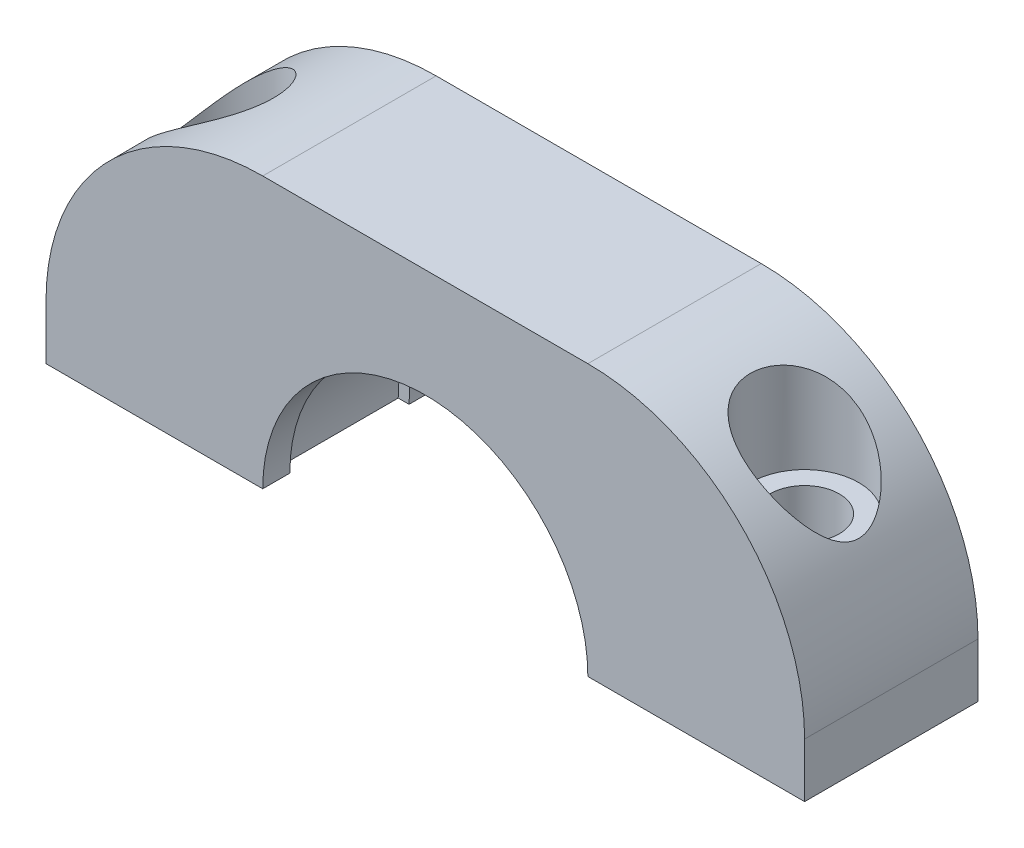
SolidWorks part; units mm, degrees
ref_plane "Front Plane" through (0, 0, 0) normal (0, 0, 1) x (1, 0, 0)
ref_plane "Top Plane" through (0, 0, 0) normal (0, 1, 0) x (1, 0, 0)
ref_plane "Right Plane" through (0, 0, 0) normal (1, 0, 0) x (0, 0, -1)
sketch "Sketch1" plane through (0, 0, 0) normal (0, 1, 0) x (1, 0, 0)
  line L1 (-17.5, -4) -> (17.5, -4)
  line L2 (-17.5, -4) -> (-17.5, 4)
  line L3 (-17.5, 4) -> (17.5, 4)
  line L4 (17.5, -4) -> (17.5, 4)
  line L5 (-17.5, -4) -> (17.5, 4) construction
  line L6 (-17.5, 4) -> (17.5, -4) construction
  point P0 (0, 0)
  dimension "D1" = 8
  dimension "D2" = 35
extrude "Boss-Extrude1" add sketch "Sketch1" along normal blind 12.5
sketch "Sketch2" plane through (0, 0, 4) normal (0, 0, 1) x (1, 0, 0)
  line L0 (-17.5, 0) -> (17.5, 0) construction
  circle A0 centre (0, 0) radius 7.5
  dimension "D1" = 15
extrude "Cut-Extrude1" cut sketch "Sketch2" against normal up to next
fillet "Fillet1" radius 10 2 edges at (17.5, 12.5, 0) (-17.5, 12.5, 0)
sketch "Sketch3" plane through (0, 0, 0) normal (0, 0, 1) x (1, 0, 0)
  circle A0 centre (0, 0) radius 8
  dimension "D1" = 16
extrude "Cut-Extrude2" cut sketch "Sketch3" against normal mid plane 5.5
sketch "Sketch4" plane through (0, 0, 0) normal (0, -1, 0) x (1, 0, 0)
  circle A0 centre (13.5, 0) radius 1.6
  circle A1 centre (-13.5, 0) radius 1.6
  dimension "D1" = 3.2
extrude "Cut-Extrude3" cut sketch "Sketch4" against normal through all
ref_plane "Plane2" through (0, 7.5, 0) normal (0, -1, 0) x (-1, 0, 0)
sketch "Sketch5" plane through (0, 7.5, 0) normal (0, -1, 0) x (-1, 0, 0)
  circle A0 centre (-13.5, 0) radius 2.5
  circle A1 centre (13.5, 0) radius 2.5
  dimension "D1" = 5
extrude "Cut-Extrude4" cut sketch "Sketch5" against normal through all
